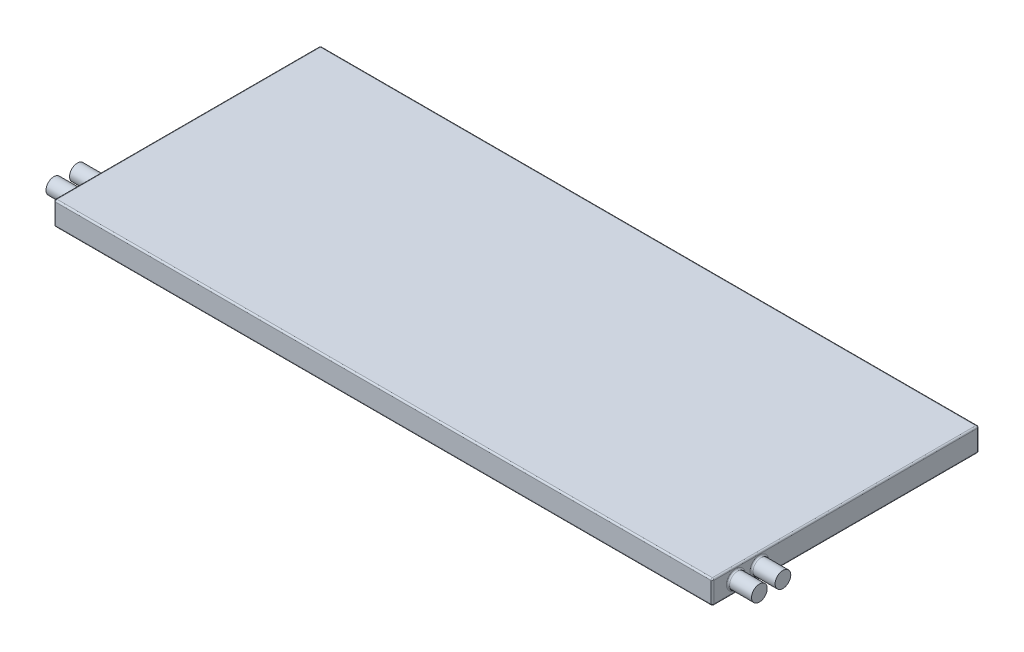
SolidWorks part; units mm, degrees
ref_plane "Front Plane" through (0, 0, 0) normal (0, 0, 1) x (1, 0, 0)
ref_plane "Top Plane" through (0, 0, 0) normal (0, 1, 0) x (1, 0, 0)
ref_plane "Right Plane" through (0, 0, 0) normal (1, 0, 0) x (0, 0, -1)
sketch "Sketch1" plane through (0, 0, 0) normal (0, 1, 0) x (1, 0, 0)
  line L1 (21, -8.5) -> (-21, -8.5)
  line L2 (21, -8.5) -> (21, 8.5)
  line L3 (21, 8.5) -> (-21, 8.5)
  line L4 (-21, -8.5) -> (-21, 8.5)
  line L5 (21, -8.5) -> (-21, 8.5) construction
  line L6 (21, 8.5) -> (-21, -8.5) construction
  point P0 (0, 0)
  dimension "D1" = 42
  dimension "D2" = 17
extrude "Boss-Extrude1" add sketch "Sketch1" along normal blind 1.5
sketch "Sketch2" plane through (-21, 0, 0) normal (-1, 0, 0) x (0, 0, 1)
  line L0 (8.5, 0.75) -> (-8.5, 0.75) construction
  line L1 (8.5, 1.5) -> (8.5, 0) construction
  line L2 (-8.5, 1.5) -> (-8.5, 0) construction
  circle A0 centre (5.5, 0.75) radius 0.5
  circle A1 centre (7, 0.75) radius 0.5
  dimension "D1" = 1
  dimension "D2" = 1.5
  dimension "D3" = 1.5
extrude "Boss-Extrude2" add sketch "Sketch2" along normal blind 1.5
mirror "Mirror1" about plane through (0, 0, 0) normal (1, 0, 0) of "Boss-Extrude2"
fillet "Fillet1" radius 0.1 16 edges at (0, 0, -8.5) (-21, 0.75, -8.5) (-21, 0, 0) (-21, 0.75, 6.5) (-21, 0.75, 5) (21, 0.75, -8.5) (21, 0, 0) (21, 0.75, 7.5) (21, 0.75, 6) (-21, 0.75, 8.5) (21, 0.75, 8.5) (0, 0, 8.5) (0, 1.5, -8.5) (21, 1.5, 0) (0, 1.5, 8.5) (-21, 1.5, 0)
